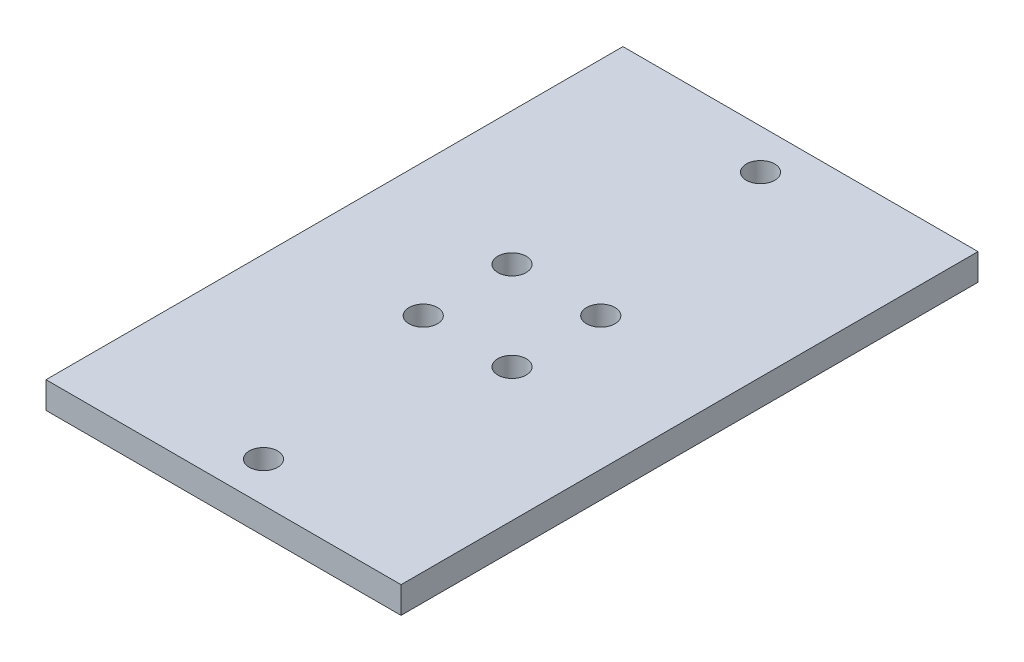
SolidWorks part; units mm, degrees
ref_plane "前视基准面" through (0, 0, 0) normal (0, 0, 1) x (1, 0, 0)
ref_plane "上视基准面" through (0, 0, 0) normal (0, 1, 0) x (1, 0, 0)
ref_plane "右视基准面" through (0, 0, 0) normal (1, 0, 0) x (0, 0, -1)
other "Configuration Table"
sketch "草图1" plane through (0, 0, 0) normal (0, 1, 0) x (1, 0, 0)
  line L0 (-10, 0) -> (10, 0) construction
  line L1 (-20, -32.5) -> (20, -32.5)
  line L2 (-20, -32.5) -> (-20, 32.5)
  line L3 (-20, 32.5) -> (20, 32.5)
  line L4 (20, -32.5) -> (20, 32.5)
  line L5 (-20, -32.5) -> (20, 32.5) construction
  line L6 (-20, 32.5) -> (20, -32.5) construction
  line L7 (-10, -10) -> (10, -10) construction
  line L8 (-10, -10) -> (-10, 10) construction
  line L9 (-10, 10) -> (10, 10) construction
  line L10 (10, -10) -> (10, 10) construction
  line L11 (-10, -10) -> (10, 10) construction
  line L12 (-10, 10) -> (10, -10) construction
  line L13 (0, 0) -> (0, 10) construction
  circle A0 centre (-5, 5) radius 1.6
  circle A1 centre (-5, -5) radius 1.6
  circle A2 centre (5, -5) radius 1.6
  circle A3 centre (5, 5) radius 1.6
  circle A4 centre (0, 28) radius 1.6
  circle A5 centre (0, -28) radius 1.6
  point P0 (0, 0)
  point P6 (0, 0)
  dimension "D5" = 3.2
  dimension "D9" = 3.2
  dimension "D1" = 65
  dimension "D2" = 40
  dimension "D3" = 20
  dimension "D4" = 20
  dimension "D6" = 10
  dimension "D7" = 10
  dimension "D8" = 28
extrude "凸台-拉伸1" add sketch "草图1" along normal blind 3
